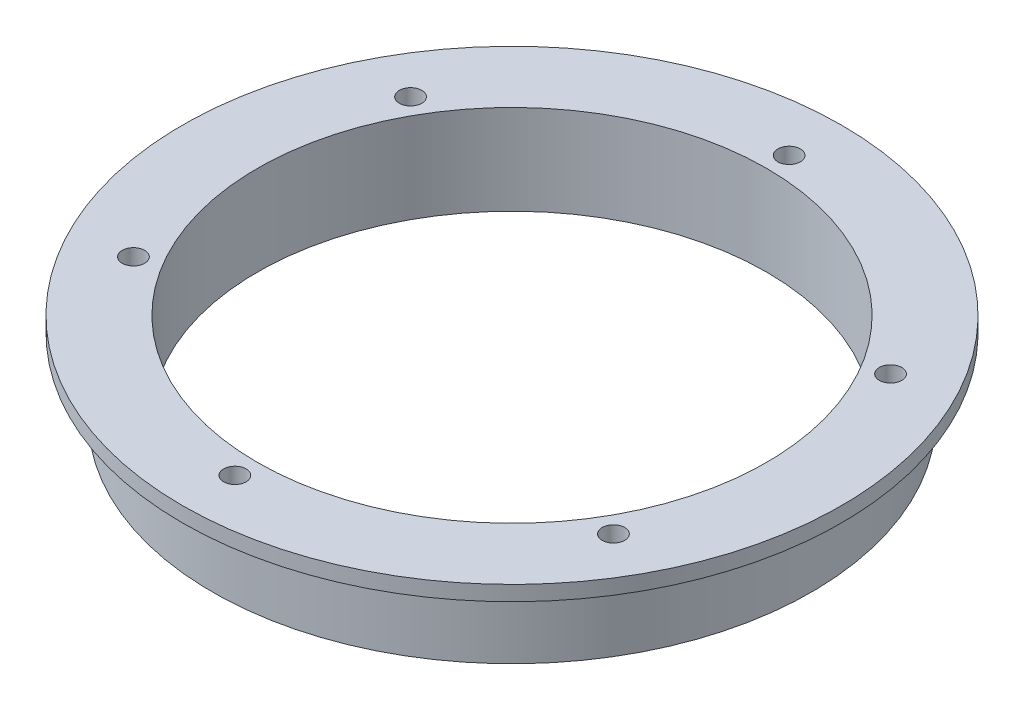
SolidWorks part; units mm, degrees
ref_plane "前视基准面" through (0, 0, 0) normal (0, 0, 1) x (1, 0, 0)
ref_plane "上视基准面" through (0, 0, 0) normal (0, 1, 0) x (1, 0, 0)
ref_plane "右视基准面" through (0, 0, 0) normal (1, 0, 0) x (0, 0, -1)
other "Configuration Table"
sketch "草图2" plane through (0, 0, 0) normal (0, 0, 1) x (1, 0, 0)
  line L0 (0, 0) -> (0, 12) construction
  line L1 (0, 12) -> (34, 12) construction
  line L2 (34, 12) -> (34, 0)
  line L3 (34, 0) -> (40, 0)
  line L4 (40, 0) -> (40, 10)
  line L5 (40, 10) -> (44, 10)
  line L6 (44, 10) -> (44, 12)
  line L7 (44, 12) -> (34, 12)
  line L8 (0, 0) -> (34, 0) construction
  dimension "D1" = 40
  dimension "D2" = 2
  dimension "D3" = 4
  dimension "D4" = 10
  dimension "D5" = 6
revolve "旋转1" add sketch "草图2" angle 360 about L0
sketch "草图4" plane through (0, 0, 0) normal (0, 1, 0) x (1, 0, 0)
  line L0 (0, 40) -> (0, 34) construction
  circle A0 centre (0, 0) radius 40 construction
  circle A1 centre (0, 0) radius 34 construction
  circle A2 centre (0, 37) radius 1.5
  circle A3 centre (32.0429, 18.5) radius 1.5
  circle A4 centre (32.0429, -18.5) radius 1.5
  circle A5 centre (0, -37) radius 1.5
  circle A6 centre (-32.0429, -18.5) radius 1.5
  circle A7 centre (-32.0429, 18.5) radius 1.5
  point P21 (0, 0)
  dimension "D1" = 3
  dimension "D2" = 6
extrude "切除-拉伸1" cut sketch "草图4" along normal through all
